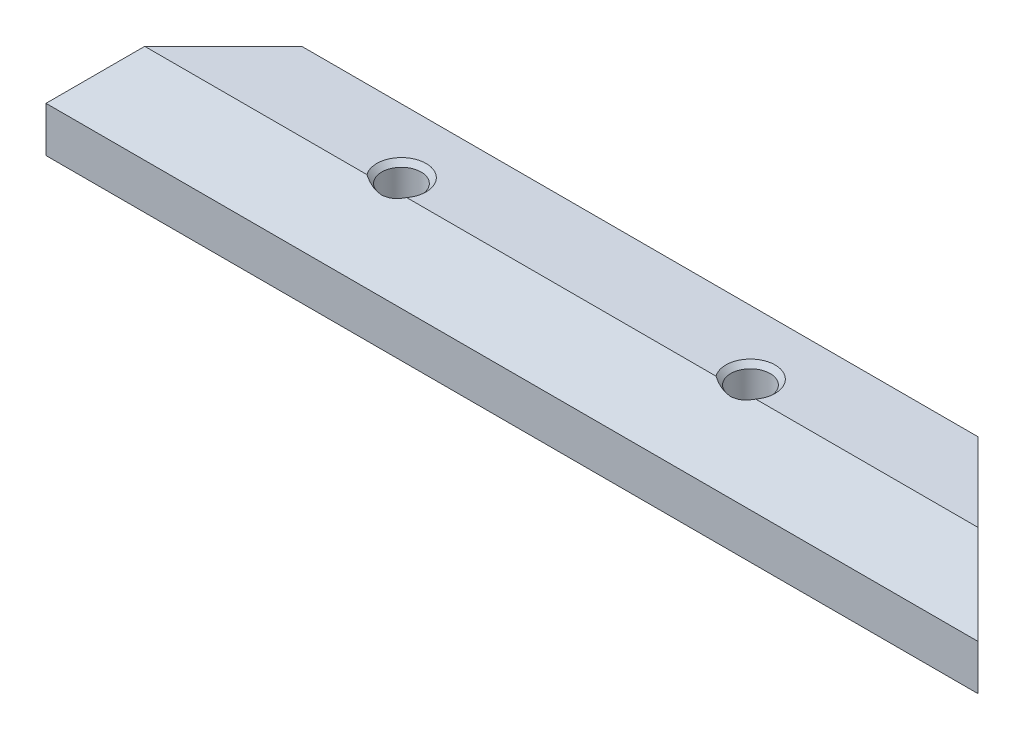
SolidWorks part; units mm, degrees
ref_plane "Front Plane" through (0, 0, 0) normal (0, 0, 1) x (1, 0, 0)
ref_plane "Top Plane" through (0, 0, 0) normal (0, 1, 0) x (1, 0, 0)
ref_plane "Right Plane" through (0, 0, 0) normal (1, 0, 0) x (0, 0, -1)
sketch "Sketch1" plane through (0, 0, 0) normal (0, 1, 0) x (1, 0, 0)
  line L0 (-94.41, 0) -> (94.41, 0)
  line L1 (-68.5, 25.91) -> (68.5, 25.91)
  line L2 (-94.41, 0) -> (-68.5, 25.91)
  line L3 (68.5, 25.91) -> (94.41, 0)
  point P4 (0, 0)
  point P8 (0, 25.91)
  dimension "D1" = 137
  dimension "D2" = 45
  dimension "D3" = 45
  dimension "D4" = 25.91
extrude "Boss-Extrude1" add sketch "Sketch1" along normal blind 3
sketch "Sketch4" plane through (0, 3, 0) normal (0, 1, 0) x (1, 0, 0)
  line L0 (0, -1000) -> (0, 49000) construction
  line L1 (-94.41, 0) -> (94.41, 0) construction
  circle A0 centre (0, 133.2) radius 120 construction
  point P7 (0, 0)
  dimension "D2" = 240
  dimension "D1" = 133.2
sketch "Sketch5" plane through (0, 3, 0) normal (0, 1, 0) x (1, 0, 0)
  line L0 (68.5, 25.91) -> (-68.5, 25.91) construction
  line L1 (-64.4969, 25.91) -> (-68.5, 25.91)
  line L2 (-68.5, 25.91) -> (-94.41, 0)
  line L3 (-94.41, 0) -> (94.41, 0)
  line L4 (94.41, 0) -> (68.5, 25.91)
  line L5 (68.5, 25.91) -> (64.4969, 25.91)
  arc A0 (-45.5273, 22.1718) -> (45.5273, 22.1718) centre (0, 133.2) ccw
  circle A1 centre (0, 133.2) radius 120 construction
  arc A2 (45.5273, 22.1718) -> (64.4969, 25.91) centre (64.4969, -24.09) cw
  arc A3 (-45.5273, 22.1718) -> (-64.4969, 25.91) centre (-64.4969, -24.09) ccw
  point P18 (53.7481, 25.91)
  point P21 (-53.7481, 25.91)
  dimension "D1" = 50
extrude "Boss-Extrude2" add sketch "Sketch5" along normal blind 12
sketch "Sketch7" plane through (0, 15, 0) normal (0, 1, 0) x (1, 0, 0)
  line L0 (-94.41, 0) -> (-68.5, 25.91)
  line L1 (-68.5, 25.91) -> (68.5, 25.91)
  line L2 (68.5, 25.91) -> (94.41, 0)
  line L3 (94.41, 0) -> (-94.41, 0)
extrude "Boss-Extrude3" add sketch "Sketch7" along normal blind 4.17
sketch "Sketch3" plane through (0, 3, 0) normal (0, 1, 0) x (1, 0, 0)
  line L0 (0, -1000) -> (0, 49000) construction
  line L1 (-988.1148, 12.955) -> (49011.8852, 12.955) construction
  line L2 (-68.5, 25.91) -> (-94.41, 0) construction
  line L3 (-35.3553, 12.955) -> (0, -22.4003) construction
  line L4 (0, -22.4003) -> (35.3553, 12.955) construction
  circle A0 centre (-35.3553, 12.955) radius 2
  circle A1 centre (35.3553, 12.955) radius 2
  point P11 (-81.455, 12.955)
  point P14 (0, -22.4003)
  dimension "D1" = 4
  dimension "D2" = 4
  dimension "D3" = 50
  dimension "D4" = 50
  dimension "D5" = 90
extrude "Cut-Extrude1" cut sketch "Sketch3" against normal through all both and the other way through all
chamfer "Chamfer1" distance 10 angle 45 1 edges at (0, 19.17, 0)
sketch "Sketch8" plane through (0, 19.17, 0) normal (0, 1, 0) x (1, 0, 0)
  circle A0 centre (-35.3553, 12.955) radius 4
  circle A1 centre (35.3553, 12.955) radius 4
  dimension "D1" = 8
  dimension "D2" = 8
extrude "Cut-Extrude2" cut sketch "Sketch8" against normal offset from surface (16.17 mm away) 3 up to face at (-35.3553, 0, -10.955)
chamfer "Chamfer2" distance 1 angle 45 2 edges at (-35.3553, 19.17, -16.955) (35.3553, 19.17, -16.955)
